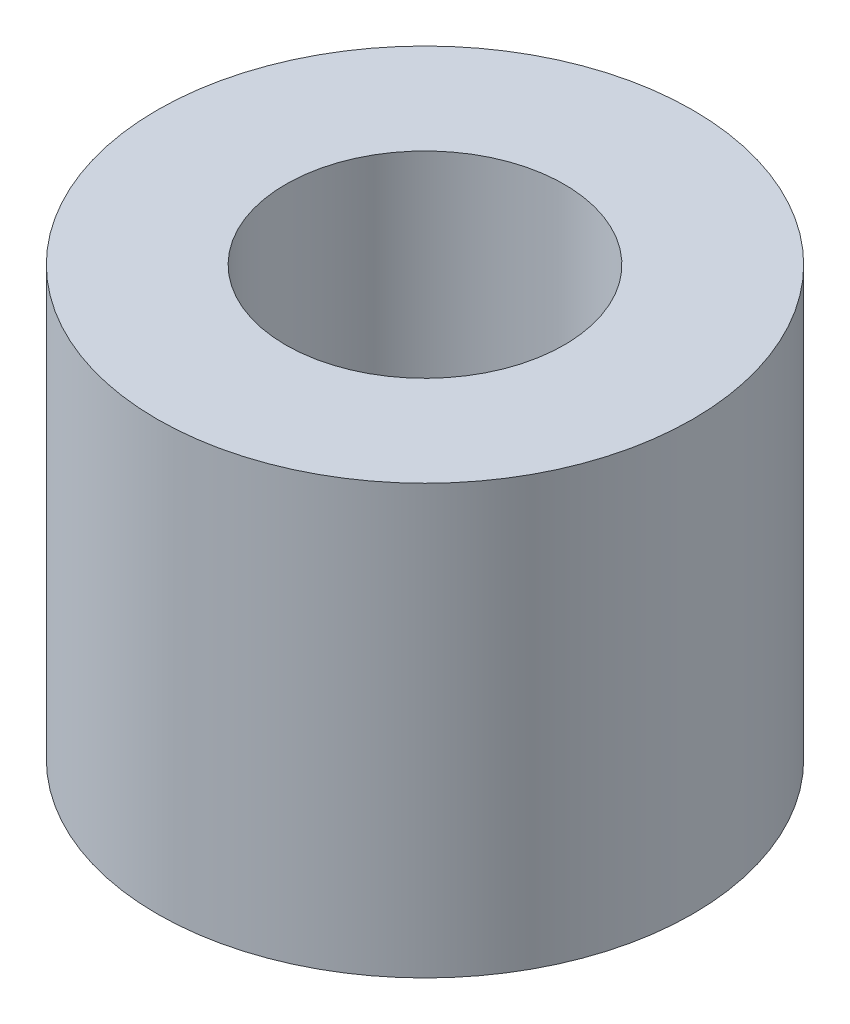
SolidWorks part; units mm, degrees
ref_plane "Front" through (0, 0, 0) normal (0, 0, 1) x (1, 0, 0)
ref_plane "Top" through (0, 0, 0) normal (0, 1, 0) x (1, 0, 0)
ref_plane "Right" through (0, 0, 0) normal (1, 0, 0) x (0, 0, -1)
sketch "Sketch1" plane through (0, 0, 0) normal (0, 1, 0) x (1, 0, 0)
  circle A0 centre (0, 0) radius 2.6
  circle A1 centre (0, 0) radius 5
  dimension "D1" = 5.2
  dimension "D2" = 10
extrude "Boss-Extrude1" add sketch "Sketch1" along normal blind 8
